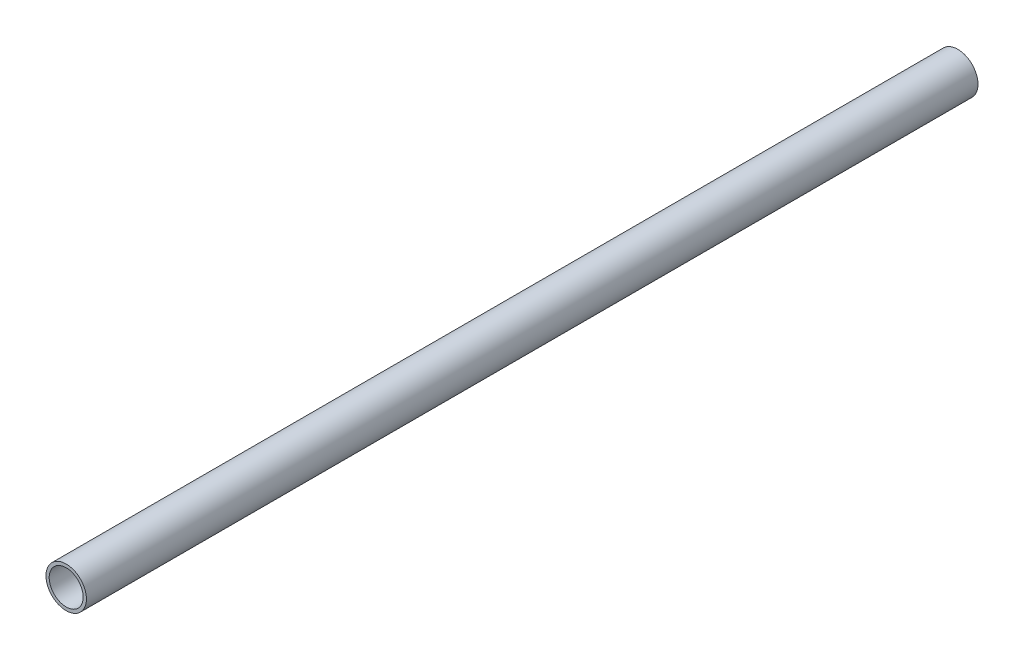
SolidWorks part; units mm, degrees
material "AISI 316 Annealed Stainless Steel Bar (SS)"
ref_plane "Front Plane" through (0, 0, 0) normal (0, 0, 1) x (1, 0, 0)
ref_plane "Top Plane" through (0, 0, 0) normal (0, 1, 0) x (1, 0, 0)
ref_plane "Right Plane" through (0, 0, 0) normal (1, 0, 0) x (0, 0, -1)
sketch "Sketch1" plane through (0, 0, 0) normal (0, 0, 1) x (1, 0, 0)
  circle A0 centre (0, 0) radius 3.175
  circle A1 centre (0, 0) radius 2.667
  dimension "D1" = 6.35
  dimension "D2" = 0.508
extrude "Boss-Extrude1" add sketch "Sketch1" along normal blind 140
